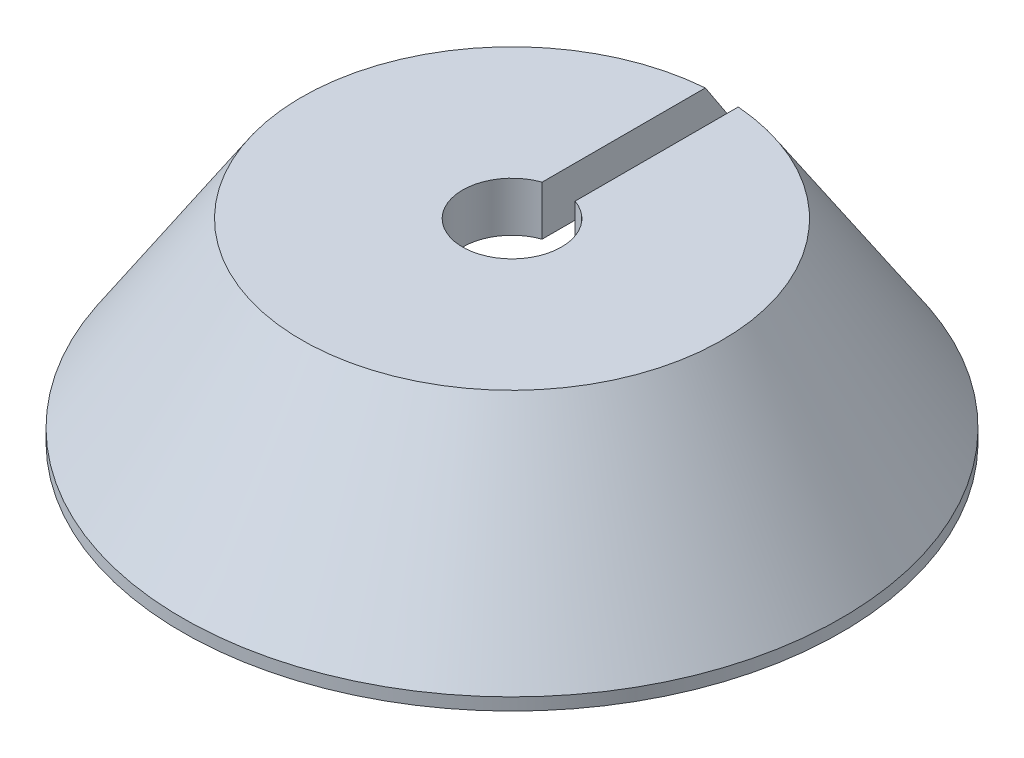
SolidWorks part; units mm, degrees
ref_plane "前视基准面" through (0, 0, 0) normal (0, 0, 1) x (1, 0, 0)
ref_plane "上视基准面" through (0, 0, 0) normal (0, 1, 0) x (1, 0, 0)
ref_plane "右视基准面" through (0, 0, 0) normal (1, 0, 0) x (0, 0, -1)
sketch "草图1" plane through (0, 0, 0) normal (0, 0, 1) x (1, 0, 0)
  line L0 (0, 5.9496) -> (0, -0.5382) construction
  line L1 (0, 0) -> (7, 0)
  line L2 (7, 0) -> (4.7, 3.5)
  line L3 (4.7, 3.5) -> (1.2, 3.5)
  line L5 (1.2, 3.5) -> (1.2, 6.5)
  line L6 (1.2, 6.5) -> (0, 6.5)
  line L7 (0, 6.5) -> (0, 0)
  point P8 (2.95, 3.5)
  point P9 (0, 0)
  dimension "D1" = 7
  dimension "D2" = 3.5
  dimension "D3" = 3.5
  dimension "D4" = 1.2
  dimension "D5" = 3
sketch "草图2" plane through (0, 0, 0) normal (0, 0, 1) x (1, 0, 0)
  line L0 (0, 6.287) -> (0, -4.7634) construction
  line L1 (0, 0) -> (8, 0)
  line L3 (0, 4.7) -> (5.108, 4.7)
  line L4 (8, 0) -> (8, 0.2992)
  line L5 (4.7, 3.5) -> (1.2, 3.5) construction
  line L6 (0, 0) -> (0, 4.7)
  line L7 (5.108, 4.7) -> (8, 0.2992)
  line L8 (7, 0) -> (4.7, 3.5) construction
  dimension "D1" = 1
  dimension "D2" = 1.2
  dimension "D3" = 1
revolve "旋转1" add sketch "草图2" angle 360 about L0
sketch "草图3" plane through (0, 0, 0) normal (0, 0, 1) x (1, 0, 0)
  line L6 (1.2, 3.5) -> (1.2, 6.5)
  line L7 (4.7, 3.5) -> (1.2, 3.5)
  line L8 (7, 0) -> (4.7, 3.5)
  line L9 (0, 0) -> (7, 0)
  line L10 (0, 6.5) -> (0, 0)
  line L11 (1.2, 6.5) -> (0, 6.5)
  line L12 (1.2, 3.5) -> (1.2, 6.5)
  line L13 (4.7, 3.5) -> (1.2, 3.5)
  line L14 (7, 0) -> (4.7, 3.5)
  line L15 (0, 0) -> (7, 0)
  line L16 (0, 6.5) -> (0, 0)
  line L17 (1.2, 6.5) -> (0, 6.5)
  dimension "D1" = 0
revolve "切除-旋转1" cut sketch "草图3" angle 360 about L0
sketch "草图4" plane through (0, 0, 0) normal (0, 0, 1) x (1, 0, 0)
  line L1 (-0.4, 5.4968) -> (0.4, 5.4968)
  line L2 (-0.4, 5.4968) -> (-0.4, -0.4477)
  line L3 (-0.4, -0.4477) -> (0.4, -0.4477)
  line L4 (0.4, 5.4968) -> (0.4, -0.4477)
  line L5 (0, 7.2522) -> (0, -1.4363) construction
  dimension "D1" = 0.8
extrude "切除-拉伸1" cut sketch "草图4" against normal blind 10
